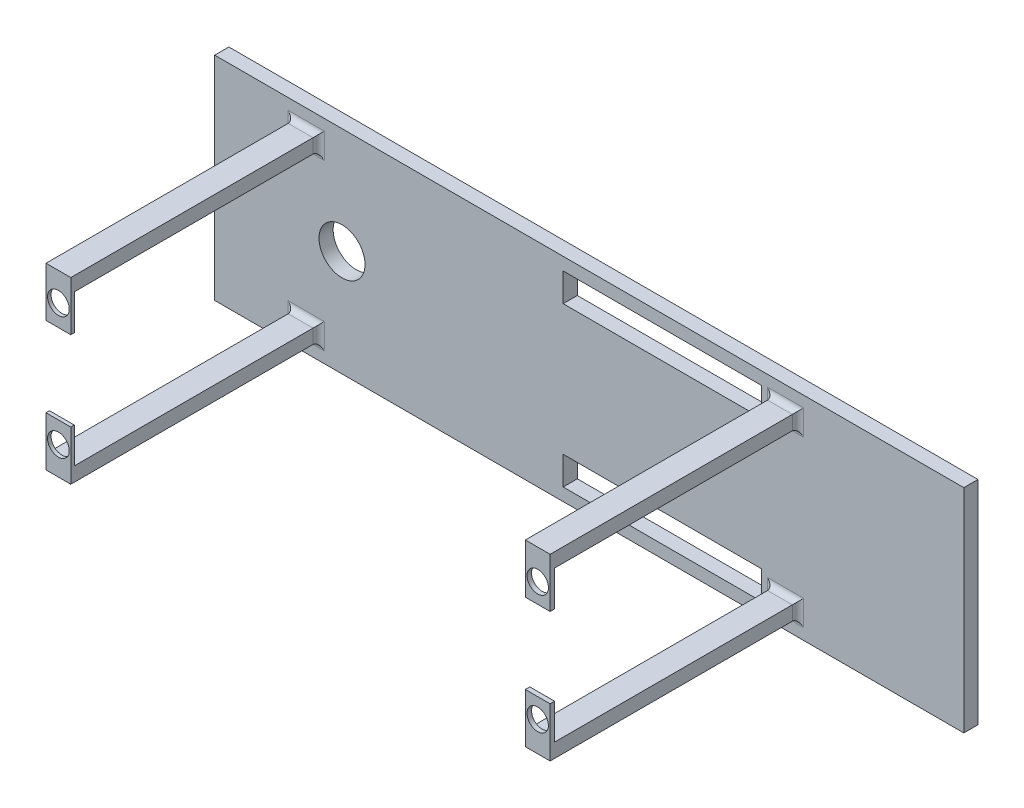
SolidWorks part; units mm, degrees
ref_plane "Front Plane" through (0, 0, 0) normal (0, 0, 1) x (1, 0, 0)
ref_plane "Top Plane" through (0, 0, 0) normal (0, 1, 0) x (1, 0, 0)
ref_plane "Right Plane" through (0, 0, 0) normal (1, 0, 0) x (0, 0, -1)
sketch "Sketch1" plane through (0, 0, 0) normal (0, 0, 1) x (1, 0, 0)
  line L1 (-52.89, -15) -> (52.89, -15)
  line L2 (-52.89, -15) -> (-52.89, 15)
  line L3 (-52.89, 15) -> (52.89, 15)
  line L4 (52.89, -15) -> (52.89, 15)
  line L5 (-52.89, -15) -> (52.89, 15) construction
  line L6 (-52.89, 15) -> (52.89, -15) construction
  point P0 (0, 0)
  dimension "D1" = 105.78
  dimension "D2" = 30
extrude "Boss-Extrude1" add sketch "Sketch1" along normal blind 2
sketch "Sketch2" plane through (0, 0, 2) normal (0, 0, 1) x (1, 0, 0)
  line L0 (-52.89, 0) -> (52.89, 0) construction
  line L1 (-52.89, 15) -> (-52.89, -15) construction
  line L2 (52.89, -15) -> (52.89, 15) construction
  line L3 (-52.89, 15) -> (-2.5543, 15) construction
  line L4 (52.89, 15) -> (-52.89, 15) construction
  line L5 (-2.5543, 0) -> (-2.5543, 11.4279) construction
  line L6 (-2.5543, 11.4279) -> (27.9931, 11.4279) construction
  circle A0 centre (-2.5543, 11.4279) radius 0.5
  dimension "D1" = 1
sketch "Sketch3" plane through (0, 0, 2) normal (0, 0, 1) x (1, 0, 0)
  line L0 (-52.89, 0) -> (52.89, 0) construction
  line L1 (-52.89, 15) -> (-52.89, -15) construction
  line L2 (52.89, -15) -> (52.89, 15) construction
sketch "Sketch5" plane through (0, 0, 2) normal (0, 0, 1) x (1, 0, 0)
  line L0 (27.6811, 0) -> (27.6811, 13) construction
  line L1 (-52.89, 0) -> (52.89, 0) construction
  line L3 (25.9696, 10.6419) -> (29.4696, 10.6419)
  line L4 (25.9696, 10.6419) -> (25.9696, 12.6419)
  line L5 (25.9696, 12.6419) -> (29.4696, 12.6419)
  line L6 (29.4696, 10.6419) -> (29.4696, 12.6419)
  line L7 (25.9696, 10.6419) -> (29.4696, 12.6419) construction
  line L8 (25.9696, 12.6419) -> (29.4696, 10.6419) construction
  dimension "D1" = 13
  dimension "D2" = 3.5
  dimension "D3" = 2
extrude "Boss-Extrude2" add sketch "Sketch5" along normal blind 35
sketch "Sketch6" plane through (0, 0, 2) normal (0, 0, 1) x (1, 0, 0)
  line L0 (25.9696, 12.6419) -> (-38.216, 12.6419) construction
  line L1 (25.9696, 12.6419) -> (25.9696, 10.6419) construction
  line L2 (29.4696, 12.6419) -> (25.9696, 12.6419) construction
  line L4 (-38.216, 12.6419) -> (-41.716, 12.6419)
  line L5 (-38.216, 12.6419) -> (-38.216, 10.6419)
  line L6 (-38.216, 10.6419) -> (-41.716, 10.6419)
  line L7 (-41.716, 12.6419) -> (-41.716, 10.6419)
  dimension "D1" = 3.5
  dimension "D2" = 2
extrude "Boss-Extrude3" add sketch "Sketch6" along normal blind 35
sketch "Sketch7" plane through (0, 10.6419, 0) normal (0, -1, 0) x (1, 0, 0)
  line L0 (-41.716, 37) -> (-41.716, 36.5045)
  line L1 (-41.716, 37) -> (-41.716, 2) construction
  line L2 (-41.716, 36.5045) -> (-38.216, 36.5045)
  line L3 (-38.216, 37) -> (-38.216, 2) construction
  line L4 (-38.216, 36.5045) -> (-38.216, 37)
  line L5 (-38.216, 37) -> (-41.716, 37)
extrude "Boss-Extrude4" add sketch "Sketch7" along normal blind 5
sketch "Sketch9" plane through (0, 10.6419, 0) normal (0, -1, 0) x (1, 0, 0)
  line L0 (25.9696, 37) -> (29.4696, 37)
  line L1 (29.4696, 37) -> (29.4696, 36.3668)
  line L2 (29.4696, 37) -> (29.4696, 2) construction
  line L3 (29.4696, 36.3668) -> (25.9696, 36.3668)
  line L4 (25.9696, 37) -> (25.9696, 2) construction
  line L5 (25.9696, 36.3668) -> (25.9696, 37)
extrude "Boss-Extrude5" add sketch "Sketch9" along normal blind 5
sketch "Sketch10" plane through (0, 0, 2) normal (0, 0, 1) x (1, 0, 0)
  line L0 (27.7196, 12.6419) -> (27.7196, 0) construction
  line L1 (29.4696, 12.6419) -> (25.9696, 12.6419) construction
  line L2 (-52.89, 0) -> (52.89, 0) construction
  line L3 (27.7196, 0) -> (27.7196, 8.4201) construction
  circle A0 centre (27.7196, 8.4201) radius 1.5102
extrude "Cut-Extrude2" cut sketch "Sketch10" along normal blind 72 contours A0
sketch "Sketch11" plane through (0, 0, 2) normal (0, 0, 1) x (1, 0, 0)
  line L0 (-39.966, 12.6419) -> (-39.966, 0) construction
  line L1 (-38.216, 12.6419) -> (-41.716, 12.6419) construction
  line L2 (-52.89, 0) -> (52.89, 0) construction
  line L3 (-39.966, 0) -> (-39.966, 8.6618) construction
  circle A0 centre (-39.966, 8.6618) radius 1.5336
extrude "Cut-Extrude3" cut sketch "Sketch11" along normal blind 42
mirror "Mirror2" about plane through (0, 0, 0) normal (0, 1, 0) of "Boss-Extrude3", "Boss-Extrude4", "Boss-Extrude5", "Cut-Extrude2", "Cut-Extrude3", "Boss-Extrude2"
sketch "Sketch12" plane through (0, 0, 2) normal (0, 0, 1) x (1, 0, 0)
  line L0 (-52.89, 0) -> (-34.9203, 0) construction
  line L1 (-52.89, 0) -> (52.89, 0) construction
  line L2 (-52.89, 0) -> (52.89, 0) construction
  circle A0 centre (-34.9203, 0) radius 3.25
  dimension "D1" = 6.5
extrude "Cut-Extrude4" cut sketch "Sketch12" against normal blind 15
fillet "Fillet1" radius 0.8 16 edges at (27.7196, 10.6419, 2) (29.4696, 11.6419, 2) (27.7196, 12.6419, 2) (25.9696, 11.6419, 2) (27.7196, -12.6419, 2) (25.9696, -11.6419, 2) (29.4696, -11.6419, 2) (27.7196, -10.6419, 2) (-41.716, -11.6419, 2) (-39.966, -10.6419, 2) (-38.216, -11.6419, 2) (-39.966, -12.6419, 2) (-39.966, 10.6419, 2) (-38.216, 11.6419, 2) (-39.966, 12.6419, 2) (-41.716, 11.6419, 2)
sketch "Sketch13" plane through (0, 0, 0) normal (0, 0, -1) x (-1, 0, 0)
  line L1 (3.6863, 13.2085) -> (-24.3138, 13.2085)
  line L2 (3.6863, 13.2085) -> (3.6863, 9.2085)
  line L3 (3.6863, 9.2085) -> (-24.3138, 9.2085)
  line L4 (-24.3138, 13.2085) -> (-24.3138, 9.2085)
  dimension "D1" = 4
extrude "Cut-Extrude5" cut sketch "Sketch13" against normal blind 10
mirror "Mirror3" about plane through (0, 0, 0) normal (0, 1, 0) of "Cut-Extrude5"
